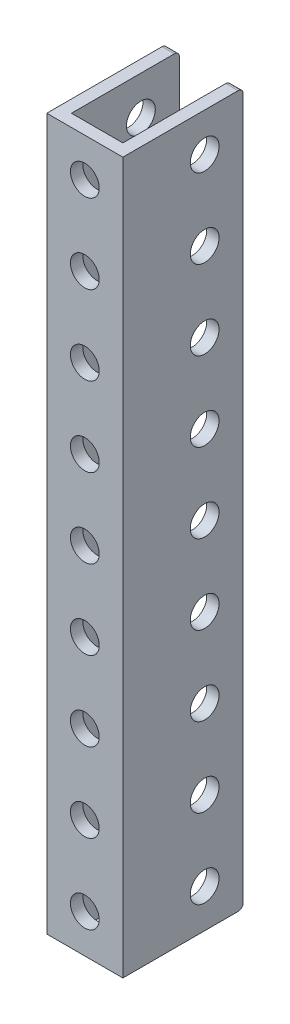
SolidWorks part; units mm, degrees
ref_plane "Front Plane" through (0, 0, 0) normal (0, 0, 1) x (1, 0, 0)
ref_plane "Top Plane" through (0, 0, 0) normal (0, 1, 0) x (1, 0, 0)
ref_plane "Right Plane" through (0, 0, 0) normal (1, 0, 0) x (0, 0, -1)
ref_plane "Plane1" through (-4.699, 0, 0) normal (-1, 0, 0) x (0, -1, 0)
sketch "Sketch1" plane through (-4.699, 0, 0) normal (-1, 0, 0) x (0, -1, 0)
  line L0 (-87.757, -13.335) -> (0, -13.335)
  line L1 (0, -13.335) -> (0, 1.524)
  line L2 (0, 1.524) -> (-87.757, 1.524)
  line L3 (-87.757, 1.524) -> (-87.757, -13.335)
extrude "Boss-Extrude1" add sketch "Sketch1" against normal blind 9.398
sketch "Sketch2" plane through (0, 0, 0) normal (0, -1, 0) x (1, 0, 0)
  line L0 (-3.175, -13.335) -> (3.175, -13.335)
  line L1 (3.175, -13.335) -> (3.175, 0)
  line L2 (3.175, 0) -> (-3.175, 0)
  line L3 (-3.175, 0) -> (-3.175, -13.335)
extrude "Cut-Extrude1" cut sketch "Sketch2" against normal through all
hole_wizard "#5 Clearance Hole1" positions "Sketch4" profile "Sketch3" hole size "#5" standard "ANSI Inch"
sketch "Sketch4" plane through (4.699, 0, 0) normal (1, 0, 0) x (0, 0, -1)
  point P0 (8.5725, 73.2155)
  point P1 (8.5725, 82.9945)
  point P2 (8.5725, 63.4365)
  point P3 (8.5725, 53.6575)
  point P4 (8.5725, 43.8785)
  point P5 (8.5725, 34.0995)
  point P6 (8.5725, 24.3205)
  point P7 (8.5725, 14.5415)
  point P8 (8.5725, 4.7625)
sketch "Sketch3" plane through (4.699, 73.2155, -8.5725) normal (0, 1, 0) x (0, 0, -1)
  line L0 (0, 0) -> (0, 1.524)
  line L1 (0, 1.524) -> (1.778, 1.524)
  line L2 (1.778, 1.524) -> (1.778, 0)
  line L5 (1.778, 0) -> (0, 0)
  line L11 (0, -6.35) -> (0, 107.95) construction
  dimension "Thru Hole Dia." = 3.556
  dimension "Thru Hole Depth" = 1.524
hole_wizard "#5 Clearance Hole2" positions "Sketch6" profile "Sketch5" hole size "#5" standard "ANSI Inch"
sketch "Sketch6" plane through (0, 0, 1.524) normal (0, 0, 1) x (1, 0, 0)
  point P0 (0, 73.2155)
  point P1 (0, 82.9945)
  point P2 (0, 63.4365)
  point P3 (0, 53.6575)
  point P4 (0, 43.8785)
  point P5 (0, 34.0995)
  point P6 (0, 24.3205)
  point P7 (0, 14.5415)
  point P8 (0, 4.7625)
sketch "Sketch5" plane through (0, 73.2155, 1.524) normal (1, 0, 0) x (0, -1, 0)
  line L0 (0, 0) -> (0, 14.859)
  line L1 (0, 14.859) -> (1.778, 14.859)
  line L2 (1.778, 14.859) -> (1.778, 0)
  line L5 (1.778, 0) -> (0, 0)
  line L11 (0, -6.35) -> (0, 107.95) construction
  dimension "Thru Hole Dia." = 3.556
  dimension "Thru Hole Depth" = 14.859
hole_wizard "#5 Clearance Hole3" positions "Sketch8" profile "Sketch7" hole size "#5" standard "ANSI Inch"
sketch "Sketch8" plane through (-3.175, 0, 0) normal (1, 0, 0) x (0, 0, -1)
  point P0 (8.5725, 73.2155)
  point P1 (8.5725, 82.9945)
  point P2 (8.5725, 63.4365)
  point P3 (8.5725, 53.6575)
  point P4 (8.5725, 43.8785)
  point P5 (8.5725, 34.0995)
  point P6 (8.5725, 24.3205)
  point P7 (8.5725, 14.5415)
  point P8 (8.5725, 4.7625)
sketch "Sketch7" plane through (-3.175, 73.2155, -8.5725) normal (0, 1, 0) x (0, 0, -1)
  line L0 (0, 0) -> (0, 1.524)
  line L1 (0, 1.524) -> (1.778, 1.524)
  line L2 (1.778, 1.524) -> (1.778, 0)
  line L5 (1.778, 0) -> (0, 0)
  line L11 (0, -6.35) -> (0, 107.95) construction
  dimension "Thru Hole Dia." = 3.556
  dimension "Thru Hole Depth" = 1.524
fillet "Fillet1" radius 0.635 4 edges at (3.937, 0, -13.335) (3.937, 87.757, -13.335) (-3.937, 87.757, -13.335) (-3.937, 0, -13.335)
